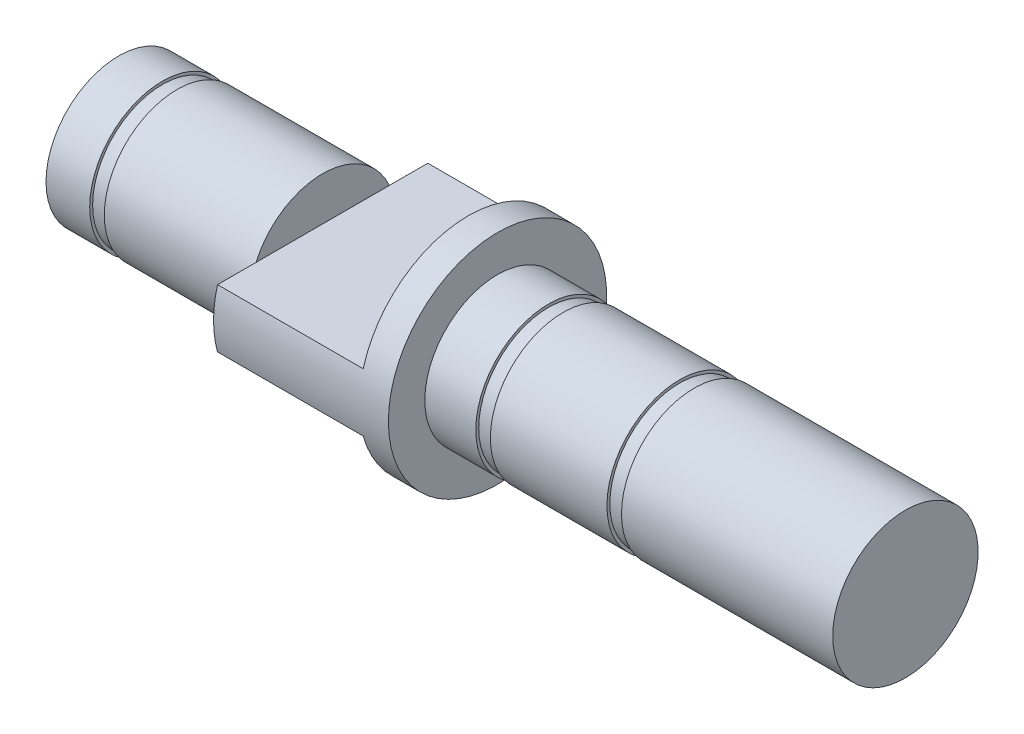
SolidWorks part; units mm, degrees
material "ASTM A36 Steel"
ref_plane "Front Plane" through (0, 0, 0) normal (0, 0, 1) x (1, 0, 0)
ref_plane "Top Plane" through (0, 0, 0) normal (0, 1, 0) x (1, 0, 0)
ref_plane "Right Plane" through (0, 0, 0) normal (1, 0, 0) x (0, 0, -1)
sketch "Sketch3" plane through (0, 0, 0) normal (0, 1, 0) x (1, 0, 0)
  line L0 (0, 0) -> (41.8214, 0) construction
  line L1 (0, 0) -> (54, 0)
  line L2 (54, 0) -> (54, 4.99)
  line L3 (54, 4.99) -> (39.5, 4.99)
  line L4 (39.5, 4.99) -> (39.5, 4.79)
  line L5 (39.5, 4.79) -> (38.5, 4.79)
  line L6 (38.5, 4.79) -> (38.5, 4.99)
  line L7 (38.5, 4.99) -> (30.5, 4.99)
  line L8 (30.5, 4.99) -> (30.5, 4.79)
  line L9 (30.5, 4.79) -> (29.5, 4.79)
  line L10 (29.5, 4.79) -> (29.5, 4.99)
  line L11 (29.5, 4.99) -> (26, 4.99)
  line L12 (26, 4.99) -> (26, 7.49)
  line L13 (26, 7.49) -> (14, 7.49)
  line L14 (14, 7.49) -> (14, 4.99)
  line L15 (14, 4.99) -> (4, 4.99)
  line L16 (4, 4.99) -> (4, 4.79)
  line L17 (4, 4.79) -> (3, 4.79)
  line L18 (3, 4.79) -> (3, 4.99)
  line L19 (3, 4.99) -> (0, 4.99)
  line L20 (0, 4.99) -> (0, 0)
  dimension "D1" = 4.99
  dimension "D2" = 0.2
  dimension "D3" = 1
  dimension "D4" = 3
  dimension "D5" = 10
  dimension "D6" = 12
  dimension "D7" = 3.5
  dimension "D8" = 8
  dimension "D9" = 54
  dimension "D10" = 2.5
revolve "Revolve1" add sketch "Sketch3" angle 360 about L0
sketch "Sketch10" plane through (14, 0, 0) normal (-1, 0, 0) x (0, 0, 1)
  line L0 (7.2284, 2) -> (-7.2284, 2)
  line L2 (7.2284, -2) -> (-7.2284, -2)
  arc A1 (-7.2284, 2) -> (7.2284, 2) centre (0, 0) cw
  arc A2 (-7.2284, -2) -> (7.2284, -2) centre (0, 0) ccw
  point P2 (0, 7.5)
  point P4 (0, -7.5)
  dimension "D1" = 4
  dimension "D3" = 7.5
  dimension "D4" = 7.5
extrude "Cut-Extrude8" cut sketch "Sketch10" against normal blind 10
